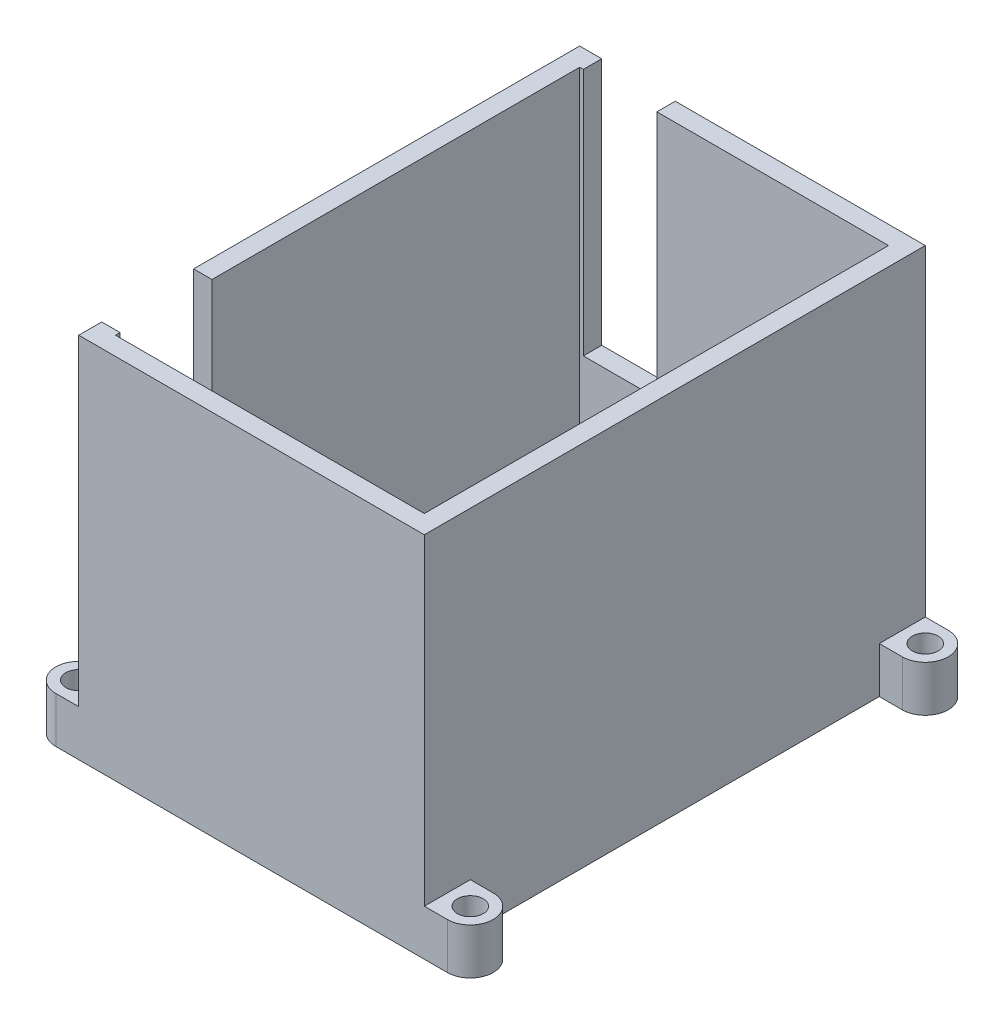
SolidWorks part; units mm, degrees
ref_plane "Front Plane" through (0, 0, 0) normal (0, 0, 1) x (1, 0, 0)
ref_plane "Top Plane" through (0, 0, 0) normal (0, 1, 0) x (1, 0, 0)
ref_plane "Right Plane" through (0, 0, 0) normal (1, 0, 0) x (0, 0, -1)
sketch "Sketch1" plane through (0, 0, 0) normal (0, 1, 0) x (1, 0, 0)
  line L1 (0, 0) -> (42.672, 0)
  line L2 (0, 0) -> (0, 64.135)
  line L3 (0, 64.135) -> (42.672, 64.135)
  line L4 (42.672, 0) -> (42.672, 64.135)
  line L5 (-2.54, 66.675) -> (45.212, 66.675)
  line L6 (-2.54, 66.675) -> (-2.54, -2.54)
  line L7 (-2.54, -2.54) -> (45.212, -2.54)
  line L8 (45.212, 66.675) -> (45.212, -2.54)
  dimension "D1" = 64.135
  dimension "D2" = 42.672
  dimension "D3" = 2.54
  dimension "D4" = 2.54
  dimension "D5" = 2.54
  dimension "D6" = 2.54
extrude "Boss-Extrude1" add sketch "Sketch1" along normal blind 50.8
sketch "Sketch2" plane through (0, 0, 0) normal (0, -1, 0) x (1, 0, 0)
  line L0 (-5.715, -3.81) -> (-2.54, -3.81)
  line L1 (-2.54, -3.81) -> (-2.54, 2.54)
  line L2 (-2.54, 2.54) -> (-5.715, 2.54)
  line L3 (-2.54, -66.675) -> (-2.54, 2.54) construction
  line L4 (-2.54, 2.54) -> (45.212, 2.54) construction
  line L7 (48.387, -60.325) -> (45.212, -60.325)
  line L9 (-2.54, -66.675) -> (-5.715, -66.675)
  line L10 (-2.54, -60.325) -> (-2.54, -66.675)
  line L11 (-5.715, -60.325) -> (-2.54, -60.325)
  line L12 (45.212, -60.325) -> (45.212, -66.675)
  line L13 (45.212, -66.675) -> (48.387, -66.675)
  line L14 (45.212, 2.54) -> (48.387, 2.54)
  line L15 (45.212, -3.81) -> (45.212, 2.54)
  line L16 (48.387, -3.81) -> (45.212, -3.81)
  arc A0 (-5.715, 2.54) -> (-5.715, -3.81) centre (-5.715, -0.635) ccw
  arc A1 (-5.715, -66.675) -> (-5.715, -60.325) centre (-5.715, -63.5) cw
  arc A2 (48.387, -66.675) -> (48.387, -60.325) centre (48.387, -63.5) ccw
  arc A3 (48.387, 2.54) -> (48.387, -3.81) centre (48.387, -0.635) cw
  dimension "D1" = 6.35
  dimension "D2" = 0
  dimension "D3" = 0
extrude "Boss-Extrude2" add sketch "Sketch2" against normal blind 6.35
hole_wizard "9/64 (0.14063) Diameter Hole1" positions "Sketch9" profile "Sketch10" hole size "9/64" standard "ANSI Inch" end condition through all
sketch "Sketch9" plane through (0, 6.35, 0) normal (0, 1, 0) x (1, 0, 0)
  point P0 (-5.715, 0.635)
  point P4 (-5.715, 63.5)
  point P7 (48.387, 63.5)
  point P10 (48.387, 0.635)
sketch "Sketch10" plane through (-5.715, 6.35, -0.635) normal (1, 0, 0) x (0, 0, 1)
  line L0 (0, 0) -> (0, 6.35)
  line L1 (0, 6.35) -> (1.786, 6.35)
  line L2 (1.786, 6.35) -> (1.786, 0)
  line L5 (1.786, 0) -> (0, 0)
  line L11 (0, -6.35) -> (0, 107.95) construction
  dimension "Thru Hole Dia." = 3.572
  dimension "Thru Hole Depth" = 6.35
sketch "Sketch11" plane through (-2.54, 0, 0) normal (-1, 0, 0) x (0, 0, 1)
  line L0 (-66.675, 50.8) -> (2.54, 50.8) construction
  line L1 (-13.335, 50.8) -> (-0.635, 50.8)
  line L2 (-13.335, 50.8) -> (-13.335, 14.605)
  line L3 (-13.335, 14.605) -> (-0.635, 14.605)
  line L4 (-0.635, 50.8) -> (-0.635, 14.605)
  line L5 (2.54, 50.8) -> (2.54, 6.35) construction
  line L6 (-60.325, 0) -> (-3.81, 0) construction
  dimension "D1" = 3.175
  dimension "D2" = 12.7
  dimension "D3" = 14.605
extrude "Cut-Extrude1" cut sketch "Sketch11" against normal blind 6.35
sketch "Sketch12" plane through (0, 0, -66.675) normal (0, 0, -1) x (-1, 0, 0)
  line L0 (-45.212, 50.8) -> (2.54, 50.8) construction
  line L1 (-0.508, 50.8) -> (-10.668, 50.8)
  line L2 (-0.508, 50.8) -> (-0.508, 16.51)
  line L3 (-0.508, 16.51) -> (-10.668, 16.51)
  line L4 (-10.668, 50.8) -> (-10.668, 16.51)
  line L5 (2.54, 50.8) -> (2.54, 6.35) construction
  line L6 (-48.387, 0) -> (5.715, 0) construction
  dimension "D1" = 10.16
  dimension "D2" = 13.208
  dimension "D3" = 16.51
extrude "Cut-Extrude2" cut sketch "Sketch12" against normal blind 6.35
